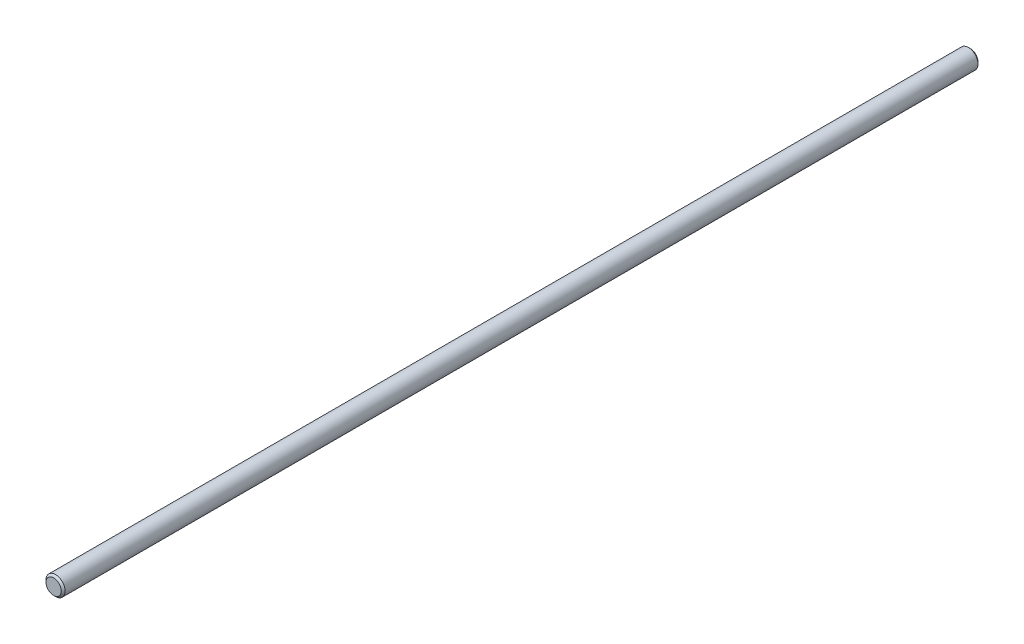
SolidWorks part; units mm, degrees
ref_plane "Front Plane" through (0, 0, 0) normal (0, 0, 1) x (1, 0, 0)
ref_plane "Top Plane" through (0, 0, 0) normal (0, 1, 0) x (1, 0, 0)
ref_plane "Right Plane" through (0, 0, 0) normal (1, 0, 0) x (0, 0, -1)
sketch "Sketch1" plane through (0, 0, 0) normal (0, 0, 1) x (1, 0, 0)
  line L0 (-1.5875, 0) -> (1.5875, 0) construction
  circle A0 centre (0, 0) radius 1.5875
  point P3 (-1.5875, 0)
  point P4 (1.5875, 0)
extrude "Extrude1" add sketch "Sketch1" along normal mid plane 152.4
chamfer "Chamfer1" distance 0.3175 angle 45 2 edges at (1.5875, 0, -76.2) (1.5875, 0, 76.2)
equation "\"D1@Chamfer1\" = \"OD@Sketch1\"*.1"
